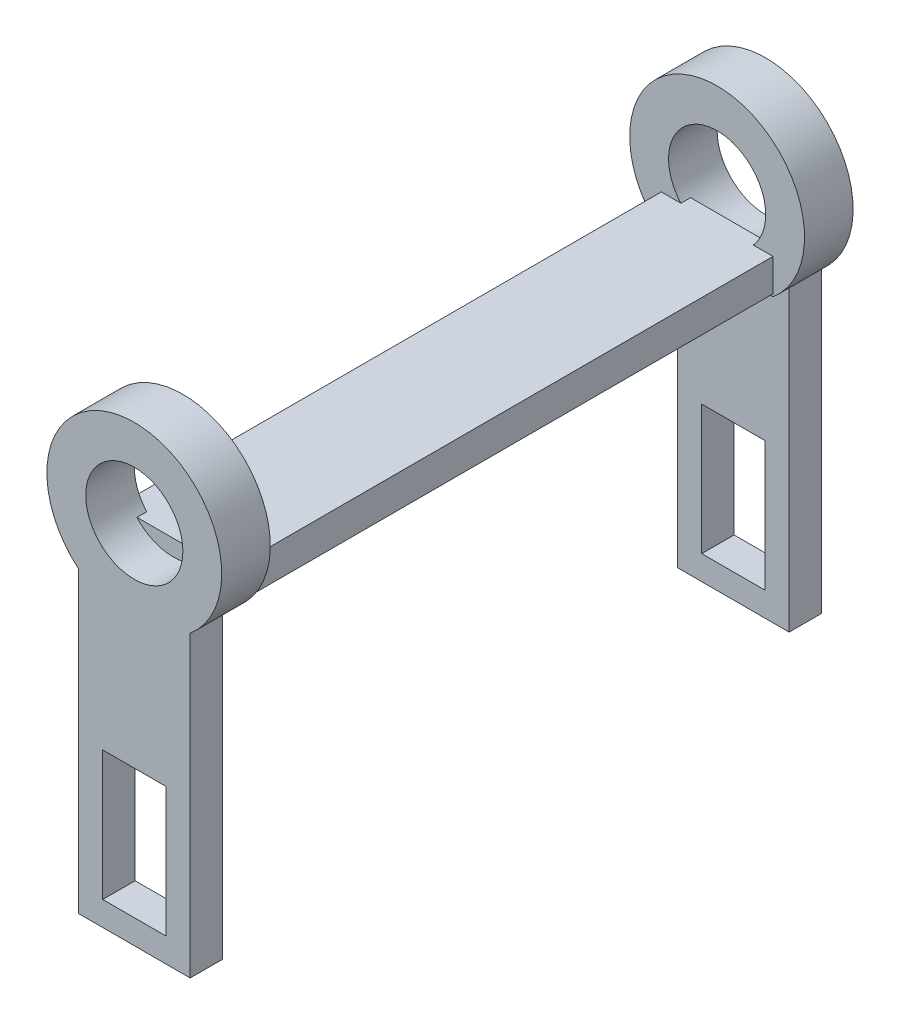
SolidWorks part; units mm, degrees
ref_plane "Plan de face" through (0, 0, 0) normal (0, 0, 1) x (1, 0, 0)
ref_plane "Plan de dessus" through (0, 0, 0) normal (0, 1, 0) x (1, 0, 0)
ref_plane "Plan de droite" through (0, 0, 0) normal (1, 0, 0) x (0, 0, -1)
sketch "Esquisse1" plane through (0, 0, 0) normal (0, 0, 1) x (1, 0, 0)
  line L0 (-17.25, 27.5) -> (17.25, 27.5)
  line L1 (-9.75, -20) -> (9.75, -20)
  line L2 (-9.75, -20) -> (-9.75, 20)
  line L3 (-9.75, 20) -> (9.75, 20)
  line L4 (9.75, -20) -> (9.75, 20)
  line L5 (-9.75, -20) -> (9.75, 20) construction
  line L6 (-9.75, 20) -> (9.75, -20) construction
  line L7 (17.25, -27.5) -> (17.25, 27.5)
  line L8 (-17.25, -27.5) -> (17.25, -27.5)
  line L9 (-17.25, -27.5) -> (-17.25, 27.5)
  point P0 (0, 0)
  dimension "D1" = 19.5
  dimension "D2" = 40
  dimension "D3" = 7.5
extrude "Boss.-Extru.1" add sketch "Esquisse1" along normal blind 10 contours L0 L7 L8 L9 | L2 L1 L4 L3
sketch "Esquisse6" plane through (0, 27.5, 0) normal (0, 1, 0) x (1, 0, 0)
  line L4 (17.25, 0) -> (-17.25, 0)
  line L5 (-17.25, 0) -> (-17.25, -10)
  line L6 (-17.25, -10) -> (17.25, -10)
  line L7 (17.25, -10) -> (17.25, 0)
  line L8 (17.25, 0) -> (-17.25, 0)
  line L9 (-17.25, 0) -> (-17.25, -10)
  line L10 (-17.25, -10) -> (17.25, -10)
  line L11 (17.25, -10) -> (17.25, 0)
  dimension "D1" = 0
extrude "Boss.-Extru.2" add sketch "Esquisse6" along normal blind 48
sketch "Esquisse7" plane through (0, 0, 10) normal (0, 0, 1) x (1, 0, 0)
  line L0 (17.25, -27.5) -> (17.25, 75.5) construction
  line L1 (-17.25, 75.5) -> (17.25, 75.5)
  line L2 (-17.25, 75.5) -> (-17.25, 65.5)
  line L3 (-17.25, 65.5) -> (17.25, 65.5)
  line L4 (17.25, 75.5) -> (17.25, 65.5)
  dimension "D1" = 10
extrude "Boss.-Extru.3" add sketch "Esquisse7" along normal blind 87.5 contours L2 L1 L4 L3
mirror "Symétrie1" about plane through (0, 0, 97.5) normal (0, 0, -1) of "Boss.-Extru.3", "Boss.-Extru.2", "Boss.-Extru.1"
sketch "Esquisse8" plane through (0, 0, 195) normal (0, 0, 1) x (1, 0, 0)
  line L0 (17.25, 75.5) -> (-17.25, 75.5)
  line L1 (17.25, 75.5) -> (-17.25, 75.5) construction
  line L2 (-17.25, 75.5) -> (-17.25, 64.7289)
  line L3 (17.25, 75.5) -> (17.25, 64.7289)
  line L4 (0, 20) -> (0, 166.5993) construction
  line L5 (-9.75, 20) -> (9.75, 20) construction
  circle A1 centre (0, 85.5) radius 15
  arc A2 (-17.25, 64.7289) -> (17.25, 64.7289) centre (0, 85.5) cw
  point P15 (0, 75.5)
  line M11 (-17.25, 75.5) -> (-17.25, -27.5)
  line M13 (17.25, -27.5) -> (17.25, 75.5)
  line M14 (17.25, 75.5) -> (-17.25, 75.5)
  dimension "D3" = 30
  dimension "D1" = 12
  dimension "D2" = 34.5
  dimension "D4" = 10
extrude "Boss.-Extru.4" add sketch "Esquisse8" against normal blind 15 contours L4 A1 A2 M14 M13 | A1 L4 A2 M11 M14
sketch "Esquisse9" plane through (0, 0, 195) normal (0, 0, 1) x (1, 0, 0)
  circle A0 centre (0, 85.5) radius 15
  arc A1 (11.1803, 75.5) -> (-11.1803, 75.5) centre (0, 85.5) ccw construction
extrude "Enlèv. mat.-Extru.1" cut sketch "Esquisse9" against normal blind 12 contours A0
sketch "Esquisse10" plane through (17.25, 0, 0) normal (-1, 0, 0) x (0, 0, 1)
  line L4 (185, 64.7289) -> (185, 65.5)
  line L5 (185, 65.5) -> (180, 65.5)
  line L6 (180, 65.5) -> (180, 64.7289)
  line L7 (180, 64.7289) -> (185, 64.7289)
  line L8 (185, 64.7289) -> (185, 65.5)
  line L9 (185, 65.5) -> (180, 65.5)
  line L10 (180, 65.5) -> (180, 64.7289)
  line L11 (180, 64.7289) -> (185, 64.7289)
  dimension "D1" = 0
extrude "Boss.-Extru.5" add sketch "Esquisse10" along normal up to next contours L8 L9 L10 L11
sketch "Esquisse11" plane through (-17.25, 0, 0) normal (-1, 0, 0) x (0, 0, 1)
  line L3 (185, 46.5731) -> (10, 46.5731)
  line L4 (185, -27.5) -> (185, 64.7289) construction
  line L5 (10, -27.5) -> (10, 65.5) construction
  line L6 (97.5, 46.5731) -> (97.5, 75.5)
  line L7 (0, 75.5) -> (180, 75.5) construction
sketch "Esquisse12" plane through (0, 75.5, 0) normal (0, 1, 0) x (1, 0, 0)
  line L6 (-17.25, -97.5) -> (17.25, -97.5)
  line L8 (17.25, -180) -> (17.25, 0) construction
ref_plane "Plan1" through (0, 0, 97.5) normal (0, 0, -1) x (-1, 0, 0)
mirror "Symétrie2" about plane through (0, 0, 97.5) normal (0, 0, -1) of "Boss.-Extru.4", "Enlèv. mat.-Extru.1", "Boss.-Extru.5"
equation "\"diametreVolant\"= 100mm"
equation "\"margeRotation\"= 10mm"
equation "\"epaisseurPlastique\"= 10mm"
equation "\"diametreVis\"= 3.5mm"
equation "\"ecartementVisMoteur\"= 19.5mm"
equation "\"diametreAxeMoteur\"= 5mm"
equation "\"longueureAxeMoteur\"= 14mm"
equation "\"hauteurMoteur\"= 17.5mm"
equation "\"nombreVisMoteur\"= 4"
equation "\"diametreMoeteur\"= 28mm"
equation "\"diametreRoulement\"= 10mm"
equation "\"ecartTrou1Servo\"= 10mm"
equation "\"epasseurVolant\"= 10mm"
equation "\"alongementServo\"= 12.5mm"
equation "\"longeurSupport\"= ( \"diametreVolant\" + 2 * \"margeRotation\" + \"alongementServo\" * 2 ) / 2 + \"epaisseurPlastique\" + 5"
equation "\"D1@Esquisse7\"=\"epaisseurPlastique\""
equation "\"hauteurSupport\"=48"
equation "\"D1@Boss.-Extru.2\"=\"hauteurSupport\""
equation "\"D1@Boss.-Extru.3\"=\"longeurSupport\""
